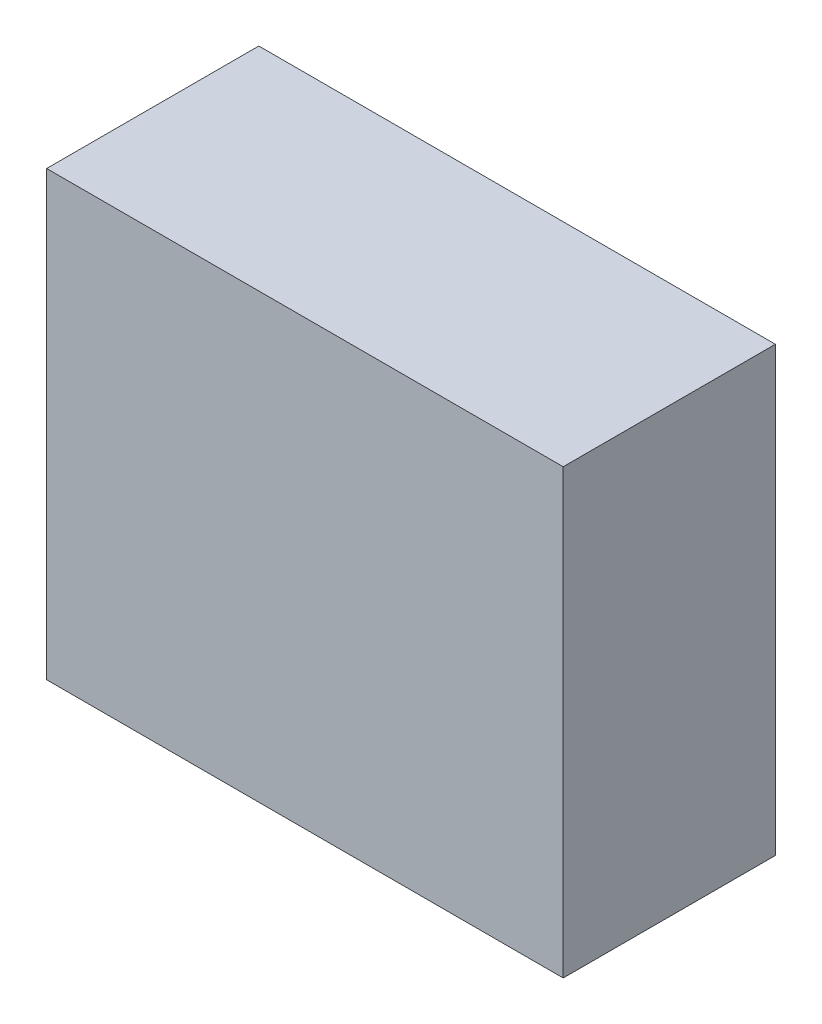
SolidWorks part; units mm, degrees
ref_plane "Front Plane" through (0, 0, 0) normal (0, 0, 1) x (1, 0, 0)
ref_plane "Top Plane" through (0, 0, 0) normal (0, 1, 0) x (1, 0, 0)
ref_plane "Right Plane" through (0, 0, 0) normal (1, 0, 0) x (0, 0, -1)
sketch "Sketch1" plane through (0, 0, 0) normal (0, 1, 0) x (1, 0, 0)
  line L1 (-4.6344, 4.3966) -> (23.3656, 4.3966)
  line L2 (-4.6344, 4.3966) -> (-4.6344, -7.1034)
  line L3 (-4.6344, -7.1034) -> (23.3656, -7.1034)
  line L4 (23.3656, 4.3966) -> (23.3656, -7.1034)
  dimension "D1" = 28
  dimension "D2" = 11.5
extrude "Boss-Extrude1" add sketch "Sketch1" along normal blind 24
